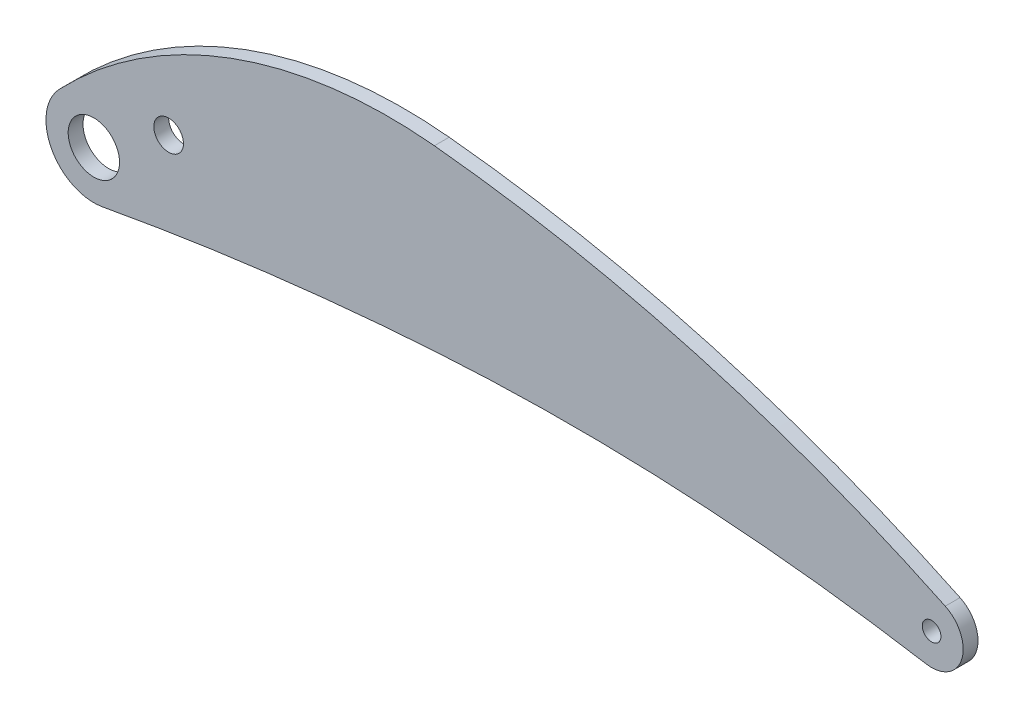
SolidWorks part; units mm, degrees
ref_plane "Front Plane" through (0, 0, 0) normal (0, 0, 1) x (1, 0, 0)
ref_plane "Top Plane" through (0, 0, 0) normal (0, 1, 0) x (1, 0, 0)
ref_plane "Right Plane" through (0, 0, 0) normal (1, 0, 0) x (0, 0, -1)
sketch "Sketch1" plane through (0, 0, 0) normal (0, 0, 1) x (1, 0, 0)
  line L0 (-20.525, 299.252) -> (-20.525, 48.5889) construction
  line L1 (379.525, 362.8114) -> (379.525, 35.4006) construction
  line L2 (0, 0) -> (379.525, 0) construction
  line L3 (145.926, 73.605) -> (145.926, -2.595) construction
  circle A0 centre (0, 0) radius 11
  arc A1 (-14.8473, 14.1716) -> (3.6998, -20.1888) centre (0, 0) ccw
  circle A2 centre (359, 0) radius 4
  arc A3 (356.7555, -13.3375) -> (364.8397, 12.1993) centre (359, 0) ccw
  circle A4 centre (359, 0) radius 20.525 construction
  arc A5 (3.6998, -20.1888) -> (145.926, -2.595) centre (225.8615, -1232.4515) cw
  arc A6 (145.926, -2.595) -> (356.7555, -13.3375) centre (205.1701, -914.102) cw
  arc A7 (-14.8473, 14.1716) -> (145.926, 73.605) centre (126.3437, -120.5935) cw
  arc A8 (145.926, 73.605) -> (364.8397, 12.1993) centre (79.6601, -583.5562) cw
  circle A9 centre (0, 0) radius 20.525 construction
  circle A10 centre (359, 0) radius 13.525 construction
  dimension "D2" = 22
  dimension "D4" = 8
  dimension "D1" = 400.05
  dimension "D6" = 76.2
  dimension "D3" = 9.525
  dimension "D5" = 9.525
extrude "Boss-Extrude1" add sketch "Sketch1" along normal blind 6.35
sketch "PocketProfile" plane through (0, 0, 6.35) normal (0, 0, 1) x (1, 0, 0)
  circle A2 centre (359, 0) radius 16.7
  arc A3 (344.2103, 7.7559) -> (342.3978, 1.8051) centre (359, 0) ccw
  circle A8 centre (0, 0) radius 23.7
  arc A9 (23.3813, -3.8734) -> (11.1333, 20.9223) centre (0, 0) ccw
  arc A12 (359.3562, 0.7441) -> (144.6519, 60.9691) centre (79.6601, -583.5562) ccw
  arc A13 (144.6519, 60.9691) -> (-5.6604, 5.4028) centre (126.3437, -120.5935) ccw
  arc A14 (-5.6604, 5.4028) -> (1.4105, -7.6968) centre (0, 0) ccw
  arc A15 (145.1023, 10.0783) -> (1.4105, -7.6968) centre (225.8615, -1232.4515) ccw
  arc A16 (358.8631, -0.8136) -> (145.1023, 10.0783) centre (205.1701, -914.102) ccw
  arc A17 (358.8631, -0.8136) -> (359.3562, 0.7441) centre (359, 0) ccw
  arc A18 (344.2103, 7.7559) -> (144.6519, 60.9691) centre (79.6601, -583.5562) ccw
  arc A19 (144.6519, 60.9691) -> (11.1333, 20.9223) centre (126.3437, -120.5935) ccw
  arc A21 (145.1023, 10.0783) -> (23.3813, -3.8734) centre (225.8615, -1232.4515) ccw
  arc A22 (342.3978, 1.8051) -> (145.1023, 10.0783) centre (205.1701, -914.102) ccw
  dimension "D1" = 12.7
  dimension "D2" = 12.7
  dimension "D3" = 12.7
sketch "Sketch2" plane through (0, 0, 6.35) normal (0, 0, 1) x (1, 0, 0)
  line L0 (32.0514, 20.599) -> (17.945, 41.7218) construction
  line L1 (17.945, 41.7218) -> (22.7186, 44.9097) construction
  circle A0 centre (32.0514, 20.599) radius 6.35
  arc A1 (145.926, 73.605) -> (-14.8473, 14.1716) centre (126.3437, -120.5935) ccw construction
  circle A2 centre (0, 0) radius 11 construction
  circle A3 centre (0, 0) radius 11 construction
  dimension "D1" = 12.7
  dimension "D2" = 25.4
  dimension "D3" = 38.1
extrude "Cut-Extrude1" cut sketch "Sketch2" against normal through all both and the other way through all
